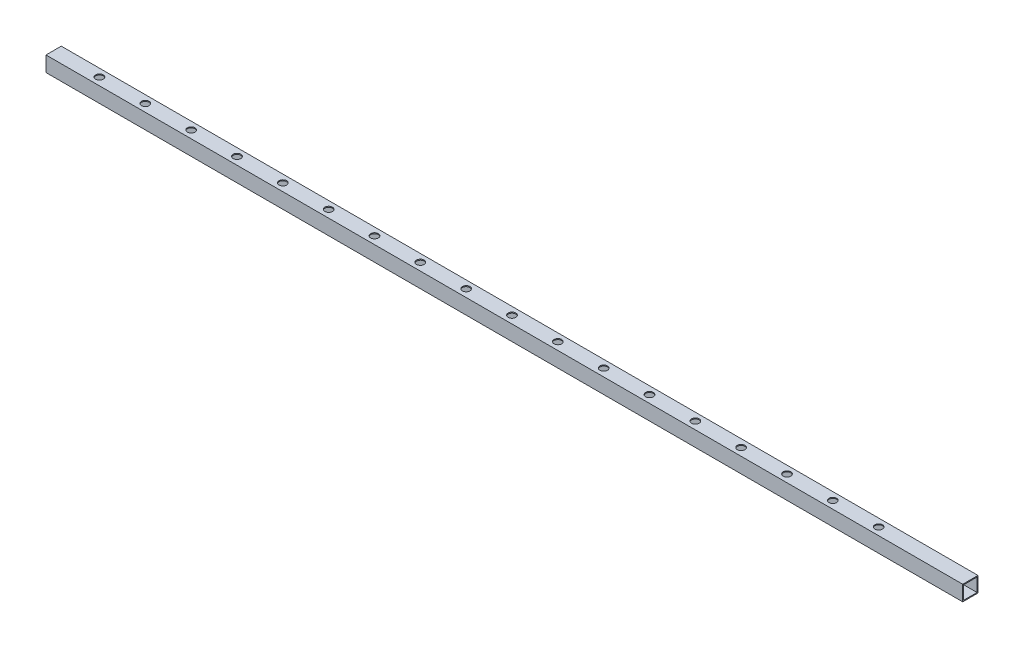
SolidWorks part; units mm, degrees
ref_plane "Front Plane" through (0, 0, 0) normal (0, 0, 1) x (1, 0, 0)
ref_plane "Top Plane" through (0, 0, 0) normal (0, 1, 0) x (1, 0, 0)
ref_plane "Right Plane" through (0, 0, 0) normal (1, 0, 0) x (0, 0, -1)
sketch "Sketch1" plane through (0, 0, 0) normal (1, 0, 0) x (0, 0, -1)
  line L0 (11.1125, -11.1125) -> (11.1125, 11.1125)
  line L1 (-12.7, -12.7) -> (12.7, -12.7)
  line L2 (-12.7, -12.7) -> (-12.7, 12.7)
  line L3 (-12.7, 12.7) -> (12.7, 12.7)
  line L4 (12.7, -12.7) -> (12.7, 12.7)
  line L5 (-12.7, -12.7) -> (12.7, 12.7) construction
  line L6 (-12.7, 12.7) -> (12.7, -12.7) construction
  line L7 (-11.1125, 11.1125) -> (11.1125, 11.1125)
  line L8 (-11.1125, -11.1125) -> (-11.1125, 11.1125)
  line L9 (-11.1125, -11.1125) -> (11.1125, -11.1125)
  point P0 (0, 0)
  dimension "D1" = 25.4
  dimension "D2" = 25.4
  dimension "D3" = 1.5875
extrude "Boss-Extrude1" add sketch "Sketch1" along normal blind 1524
hole_wizard "1/2 (0.5) Diameter Hole1" positions "Sketch2" profile "Sketch3" hole size "1/2" standard "ANSI Inch"
sketch "Sketch2" plane through (0, 12.7, 0) normal (0, 1, 0) x (1, 0, 0)
  line L0 (1524, 12.7) -> (1524, -12.7) construction
  line L1 (1524, 12.7) -> (0, 12.7) construction
  point P0 (1371.6, 0)
  dimension "D1" = 152.4
  dimension "D2" = 12.7
sketch "Sketch3" plane through (1371.6, 12.7, 0) normal (1, 0, 0) x (0, 0, 1)
  line L0 (0, 0) -> (0, 1.5875)
  line L1 (0, 1.5875) -> (6.35, 1.5875)
  line L2 (6.35, 1.5875) -> (6.35, 0)
  line L5 (6.35, 0) -> (0, 0)
  line L11 (0, -6.35) -> (0, 107.95) construction
  dimension "Thru Hole Dia." = 12.7
  dimension "Thru Hole Depth" = 1.5875
pattern_linear "LPattern1" count 18 spacing 76.2 along (-1, 0, 0) of "1/2 (0.5) Diameter Hole1"
